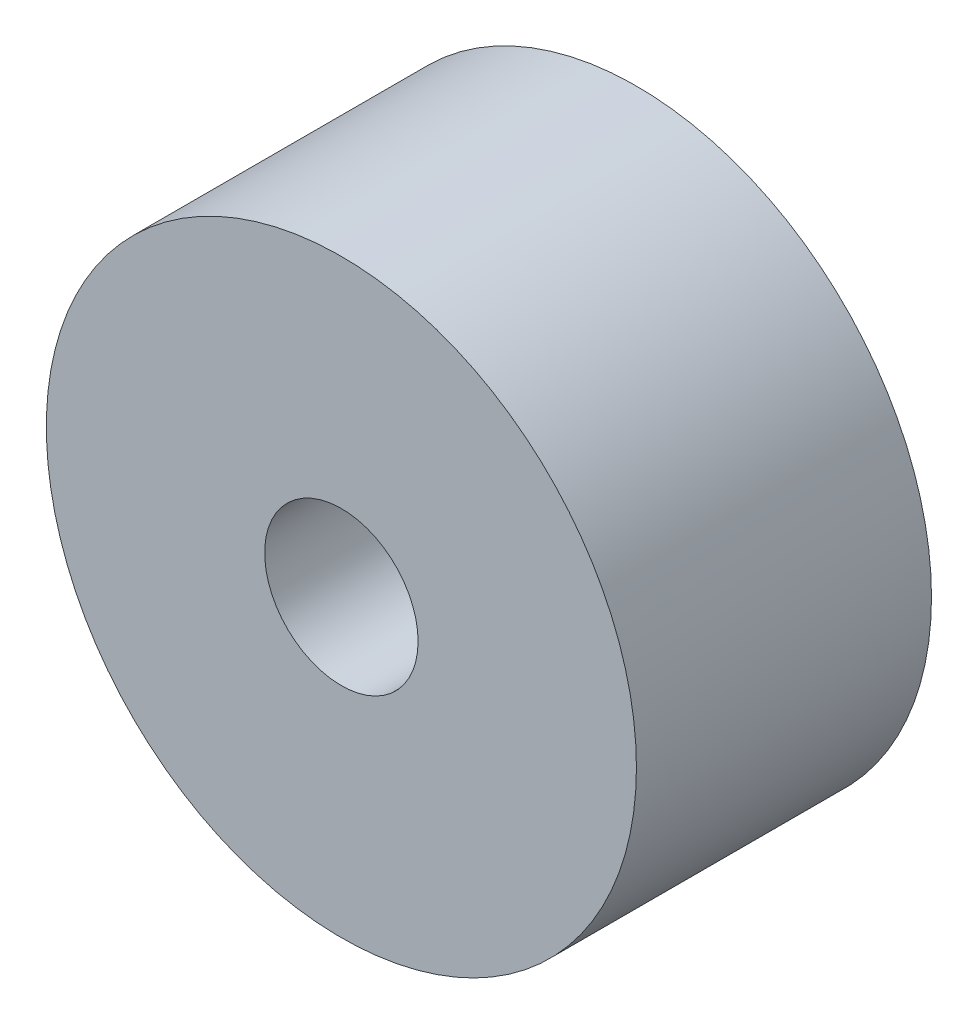
SolidWorks part; units mm, degrees
ref_plane "Front Plane" through (0, 0, 0) normal (0, 0, 1) x (1, 0, 0)
ref_plane "Top Plane" through (0, 0, 0) normal (0, 1, 0) x (1, 0, 0)
ref_plane "Right Plane" through (0, 0, 0) normal (1, 0, 0) x (0, 0, -1)
sketch "Sketch1" plane through (0, 0, 0) normal (0, 0, 1) x (1, 0, 0)
  circle A0 centre (0, 0) radius 1.3
  circle A1 centre (0, 0) radius 5
  dimension "D1" = 10
  dimension "D2" = 2.6
extrude "Boss-Extrude1" add sketch "Sketch1" along normal blind 5
